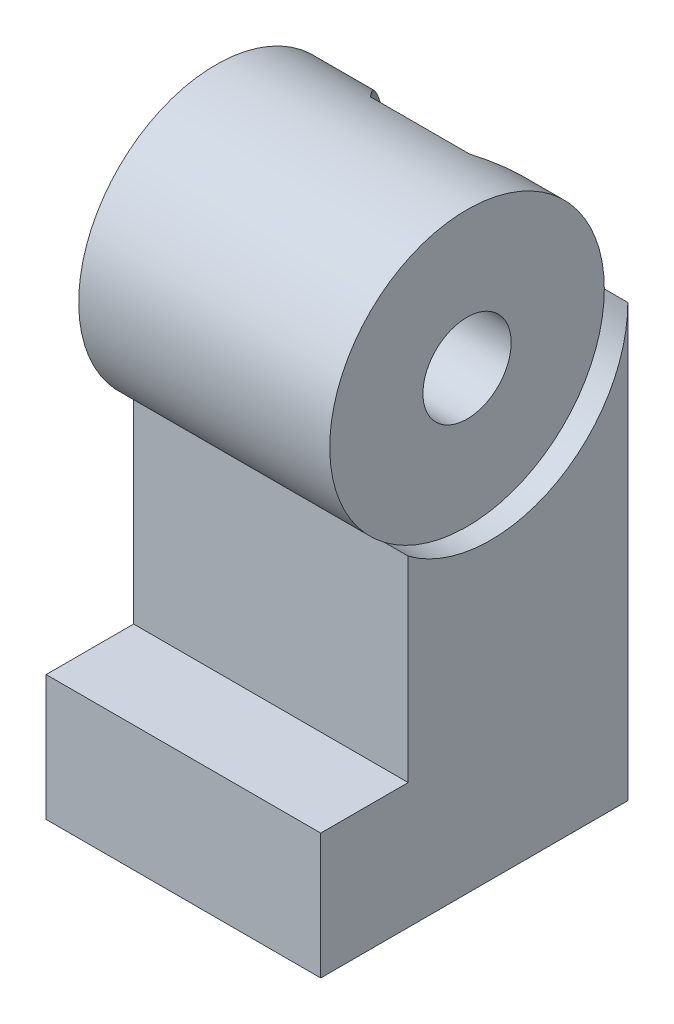
SolidWorks part; units mm, degrees
ref_plane "Front Plane" through (0, 0, 0) normal (0, 0, 1) x (1, 0, 0)
ref_plane "Top Plane" through (0, 0, 0) normal (0, 1, 0) x (1, 0, 0)
ref_plane "Right Plane" through (0, 0, 0) normal (1, 0, 0) x (0, 0, -1)
sketch "Sketch1" plane through (0, 0, 0) normal (1, 0, 0) x (0, 0, -1)
  line L0 (7.83, 0) -> (7.83, 11)
  line L1 (2.23, 3.2) -> (2.23, 8.2)
  line L2 (0, 0) -> (7.83, 0)
  line L6 (2.23, 3.2) -> (0, 3.2)
  line L7 (0, 3.2) -> (0, 0)
  arc A4 (2.23, 8.2) -> (7.83, 11) centre (4.33, 11) cw
  dimension "D3" = 11
  dimension "D1" = 5.6
  dimension "D2" = 3.5
  dimension "D4" = 7.83
  dimension "D5" = 3.2
extrude "Boss-Extrude1" add sketch "Sketch1" along normal blind 7
sketch "Sketch2" plane through (7, 0, 0) normal (1, 0, 0) x (0, 0, -1)
  circle A0 centre (4.33, 11) radius 3.5
  arc A1 (7.83, 11) -> (2.23, 8.2) centre (4.33, 11) ccw construction
  dimension "D1" = 7
  dimension "D2" = 0
extrude "Cut-Extrude1" cut sketch "Sketch2" against normal blind 0.6
sketch "Sketch3" plane through (6.4, 0, 0) normal (1, 0, 0) x (0, 0, -1)
  circle A0 centre (4.33, 11) radius 1.125
  dimension "D1" = 2.25
extrude "Cut-Extrude2" cut sketch "Sketch3" against normal blind 4
sketch "Sketch4" plane through (0, 0, -7.83) normal (0, 0, -1) x (-1, 0, 0)
  line L0 (-3.5, 0) -> (-3.5, 16.6823) construction
  line L1 (-7, 0) -> (0, 0) construction
  circle A0 centre (-3.5, 3.9) radius 2.5
  circle A2 centre (-3.5, 11.9) radius 2.5
  dimension "D2" = 5
  dimension "D4" = 5
  dimension "D6" = 8
  dimension "D1" = 3.9
  dimension "D3" = 0
  dimension "D5" = 0
extrude "Cut-Extrude3" cut sketch "Sketch4" against normal blind 1.8
sketch "Sketch5" plane through (0, 0, 0) normal (0, -1, 0) x (1, 0, 0)
  line L0 (1, -1.4) -> (6, -1.4)
  line L1 (6, -1.4) -> (6, -6.4)
  line L2 (6, -6.4) -> (1, -6.4)
  line L3 (1, -6.4) -> (1, -1.4)
  line L4 (7, 0) -> (7, -7.83) construction
  line L5 (7, 0) -> (0, 0) construction
  dimension "D1" = 5
  dimension "D2" = 5
  dimension "D3" = 1
  dimension "D4" = 1.4
extrude "Cut-Extrude4" cut sketch "Sketch5" against normal blind 2.2
sketch "Sketch7" plane through (0, 0, 0) normal (0, -1, 0) x (1, 0, 0)
  line L0 (1, -3.1) -> (6, -3.1)
  line L1 (1, -1.4) -> (1, -6.4) construction
  line L2 (6, -6.4) -> (6, -1.4) construction
  line L3 (6, -3.1) -> (6, -6.4)
  line L4 (6, -6.4) -> (1, -6.4)
  line L5 (1, -6.4) -> (1, -3.1)
  dimension "D1" = 3.3
extrude "Cut-Extrude5" cut sketch "Sketch7" against normal blind 9
sketch "Sketch8" plane through (0, 0, -6.03) normal (0, 0, -1) x (-1, 0, 0)
  line L2 (-4.4, 13.1594) -> (-4.4, 9.5676)
  line L4 (-4.4, 13.1594) -> (-1.3404, 13.1594)
  line L5 (-2.2403, 14.0594) -> (-4.7597, 14.0594) construction
  line L6 (-1.3404, 13.1594) -> (-1.3404, 10.6406)
  arc A1 (-5.8324, 11) -> (-1.1676, 11) centre (-3.5, 11.9) ccw construction
  arc A4 (-4.7597, 14.0594) -> (-5.8324, 11) centre (-3.5, 11.9) ccw construction
  arc A5 (-4.7597, 14.0594) -> (-2.2403, 14.0594) centre (-3.5, 11.9) ccw construction
  arc A6 (-1.3404, 10.6406) -> (-4.4, 9.5676) centre (-3.5, 11.9) cw
  dimension "D2" = 0.9
  dimension "D3" = 2.5
  dimension "D1" = 0.9
extrude "Cut-Extrude6" cut sketch "Sketch8" against normal blind 3
